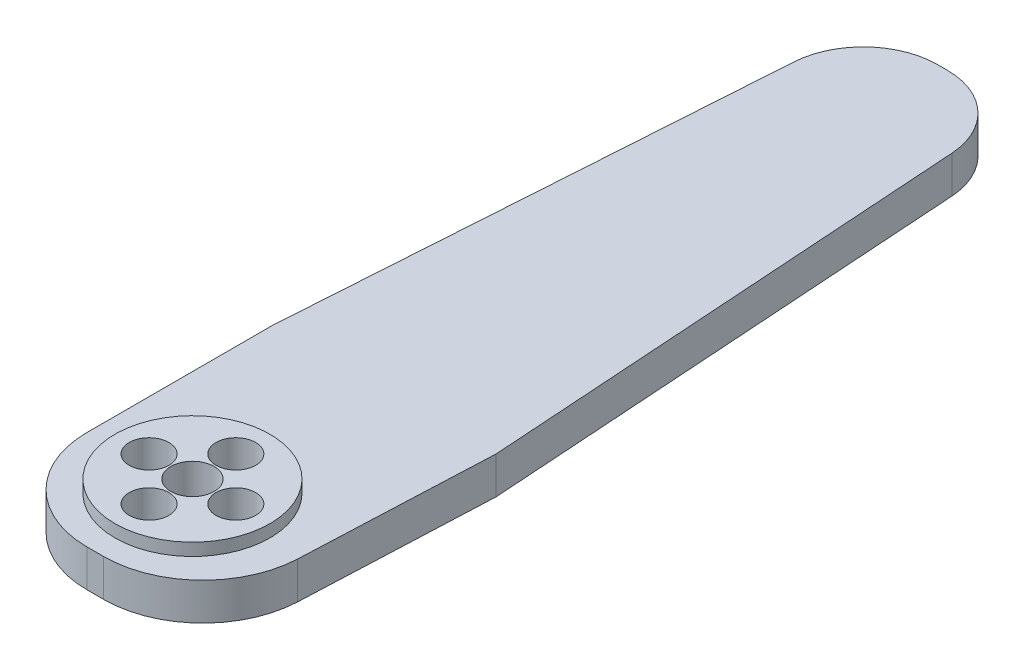
SolidWorks part; units mm, degrees
ref_plane "Front Plane" through (0, 0, 0) normal (0, 0, 1) x (1, 0, 0)
ref_plane "Top Plane" through (0, 0, 0) normal (0, 1, 0) x (1, 0, 0)
ref_plane "Right Plane" through (0, 0, 0) normal (1, 0, 0) x (0, 0, -1)
sketch "S_prism1" plane through (0, 0, 0) normal (0, 1, 0) x (1, 0, 0)
  line L0 (-1, -16) -> (1.6805, -16)
  line L1 (17.6654, -0.695) -> (19, 30)
  line L2 (19, 30) -> (13.7468, 108.7982)
  line L3 (1.7734, 120) -> (0.2266, 120)
  line L4 (-11.7468, 108.7982) -> (-17, 30)
  line L5 (-17, 30) -> (-17, 0)
  arc A0 (-17, 0) -> (-1, -16) centre (-1, 0) ccw
  arc A1 (1.6805, -16) -> (17.6654, -0.695) centre (1.6805, 0) ccw
  arc A2 (13.7468, 108.7982) -> (1.7734, 120) centre (1.7735, 108.0001) ccw
  arc A3 (0.2266, 120) -> (-11.7468, 108.7982) centre (0.2265, 108.0001) ccw
extrude "Boss_1" add sketch "S_prism1" along normal blind 6
ref_plane "PY_p6_000" through (0, 6, 0) normal (0, 1, 0) x (1, 0, 0)
sketch "S_cyl2" plane through (0, 6, 0) normal (0, 1, 0) x (1, 0, 0)
  circle A0 centre (0, 0) radius 12.5
  dimension "D1_S_cyl2" = 25
extrude "Boss_2" add sketch "S_cyl2" along normal blind 2
ref_plane "PY_m0_100" through (0, -0.1, 0) normal (0, 1, 0) x (1, 0, 0)
sketch "S_hole3" plane through (0, -0.1, 0) normal (0, 1, 0) x (1, 0, 0)
  circle A0 centre (0, 0) radius 3.5
  dimension "D1_S_hole3" = 7
extrude "Hole_3" cut sketch "S_hole3" along normal blind 8.2
sketch "S_hole4" plane through (0, -0.1, 0) normal (0, 1, 0) x (1, 0, 0)
  circle A0 centre (7, 0) radius 1.7
  dimension "D1_S_hole4" = 3.4
  dimension "P2" = 7
extrude "Hole_4" cut sketch "S_hole4" along normal blind 8.2
sketch "S_hole5" plane through (0, -0.1, 0) normal (0, 1, 0) x (1, 0, 0)
  circle A0 centre (0, -7) radius 1.7
  dimension "D1_S_hole5" = 3.4
  dimension "P2" = 7
extrude "Hole_5" cut sketch "S_hole5" along normal blind 8.2
sketch "S_hole6" plane through (0, -0.1, 0) normal (0, 1, 0) x (1, 0, 0)
  circle A0 centre (-7, 0) radius 1.7
  dimension "D1_S_hole6" = 3.4
  dimension "P2" = 7
extrude "Hole_6" cut sketch "S_hole6" along normal blind 8.2
sketch "S_hole7" plane through (0, -0.1, 0) normal (0, 1, 0) x (1, 0, 0)
  circle A0 centre (0, 7) radius 1.7
  dimension "D1_S_hole7" = 3.4
  dimension "P2" = 7
extrude "Hole_7" cut sketch "S_hole7" along normal blind 8.2
ref_plane "PY_p3_000" through (0, 3, 0) normal (0, 1, 0) x (1, 0, 0)
sketch "S_hole8" plane through (0, 3, 0) normal (0, 1, 0) x (1, 0, 0)
  circle A0 centre (7, 0) radius 3.2
  dimension "D1_S_hole8" = 6.4
  dimension "P2" = 7
extrude "Hole_8" cut sketch "S_hole8" along normal blind 5.1
sketch "S_hole9" plane through (0, 3, 0) normal (0, 1, 0) x (1, 0, 0)
  circle A0 centre (0, -7) radius 3.2
  dimension "D1_S_hole9" = 6.4
  dimension "P2" = 7
extrude "Hole_9" cut sketch "S_hole9" along normal blind 5.1
sketch "S_hole10" plane through (0, 3, 0) normal (0, 1, 0) x (1, 0, 0)
  circle A0 centre (-7, 0) radius 3.2
  dimension "D1_S_hole10" = 6.4
  dimension "P2" = 7
extrude "Hole_10" cut sketch "S_hole10" along normal blind 5.1
sketch "S_hole11" plane through (0, 3, 0) normal (0, 1, 0) x (1, 0, 0)
  circle A0 centre (0, 7) radius 3.2
  dimension "D1_S_hole11" = 6.4
  dimension "P2" = 7
extrude "Hole_11" cut sketch "S_hole11" along normal blind 5.1
equation "\"plate_t\" = 3"
equation "\"clearance\" = 0.5"
